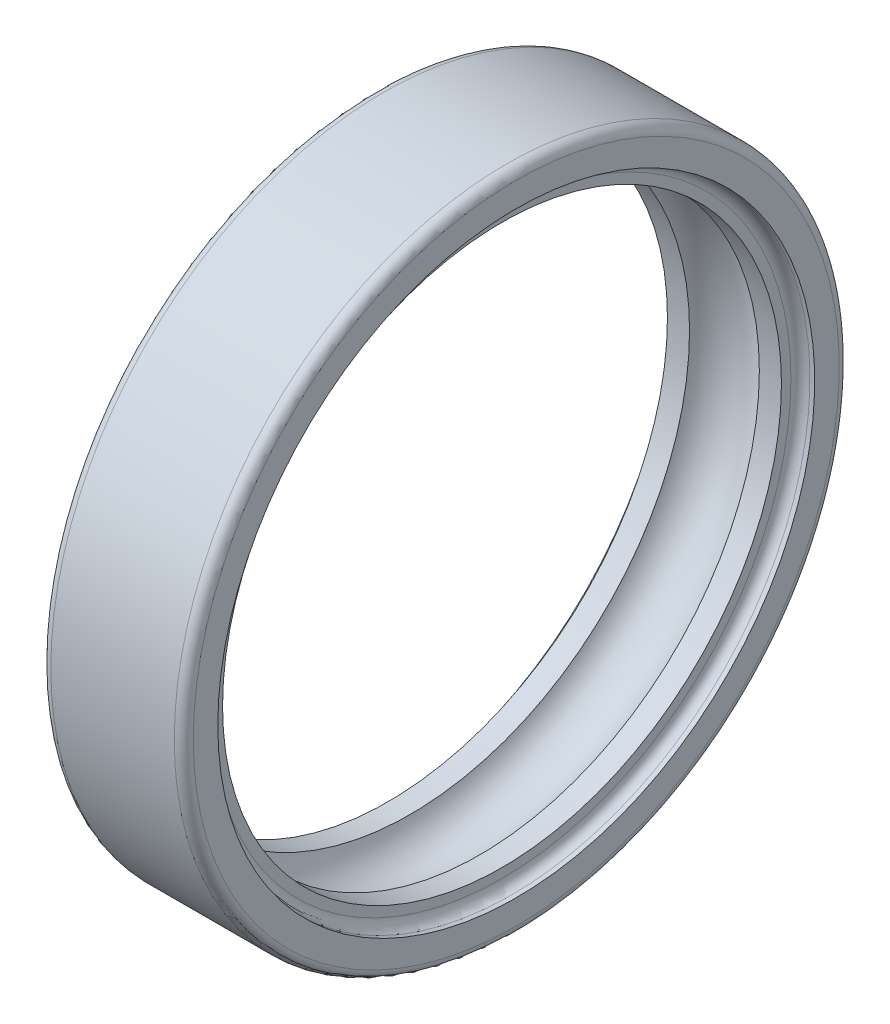
SolidWorks part; units mm, degrees
ref_plane "Front Plane" through (0, 0, 0) normal (0, 0, 1) x (1, 0, 0)
ref_plane "Top Plane" through (0, 0, 0) normal (0, 1, 0) x (1, 0, 0)
ref_plane "Right Plane" through (0, 0, 0) normal (1, 0, 0) x (0, 0, -1)
ref_plane "Plane1" through (0, 0, 0) normal (0, 0, 1) x (1, 0, 0)
sketch "Sketch1" plane through (0, 0, 0) normal (0, 0, 1) x (1, 0, 0)
  line L0 (0, 20.4) -> (0, 18.85)
  line L1 (0, 18.85) -> (0.3, 18.85)
  line L2 (0.9, 18.25) -> (0.9, 17.65)
  line L3 (0.9, 17.65) -> (2.2956, 17.65)
  line L4 (6.7044, 17.65) -> (8.1, 17.65)
  line L5 (8.1, 17.65) -> (8.1, 18.25)
  line L6 (8.7, 18.85) -> (9, 18.85)
  line L7 (9, 18.85) -> (9, 20.4)
  line L8 (8.4, 21) -> (0.6, 21)
  line L9 (50, 0) -> (-50, 0) construction
  arc A0 (0.3, 18.85) -> (0.9, 18.25) centre (0.3, 18.25) cw
  arc A1 (2.2956, 17.65) -> (6.7044, 17.65) centre (4.5, 16.75) cw
  arc A2 (8.1, 18.25) -> (8.7, 18.85) centre (8.7, 18.25) cw
  arc A3 (9, 20.4) -> (8.4, 21) centre (8.4, 20.4) ccw
  arc A4 (0.6, 21) -> (0, 20.4) centre (0.6, 20.4) ccw
revolve "Revolve1" add sketch "Sketch1" angle 360 about L9
ref_plane "Plane2" through (0, 0, 0) normal (0, 0, 1) x (1, 0, 0)
sketch "Sketch2" plane through (0, 0, 0) normal (0, 0, 1) x (1, 0, 0)
  line L0 (0, 20.4) -> (0, 18.85)
  line L1 (0, 18.85) -> (0.3, 18.85)
  line L2 (0.9, 18.25) -> (0.9, 17.65)
  line L3 (0.9, 17.65) -> (2.2956, 17.65)
  line L4 (6.7044, 17.65) -> (8.1, 17.65)
  line L5 (8.1, 17.65) -> (8.1, 18.25)
  line L6 (8.7, 18.85) -> (9, 18.85)
  line L7 (9, 18.85) -> (9, 20.4)
  line L8 (8.4, 21) -> (0.6, 21)
  line L9 (50, 0) -> (-50, 0) construction
  arc A0 (0.3, 18.85) -> (0.9, 18.25) centre (0.3, 18.25) cw
  arc A1 (2.2956, 17.65) -> (6.7044, 17.65) centre (4.5, 16.75) cw
  arc A2 (8.1, 18.25) -> (8.7, 18.85) centre (8.7, 18.25) cw
  arc A3 (9, 20.4) -> (8.4, 21) centre (8.4, 20.4) ccw
  arc A4 (0.6, 21) -> (0, 20.4) centre (0.6, 20.4) ccw
revolve "Revolve2" add sketch "Sketch2" angle 360 about L9
